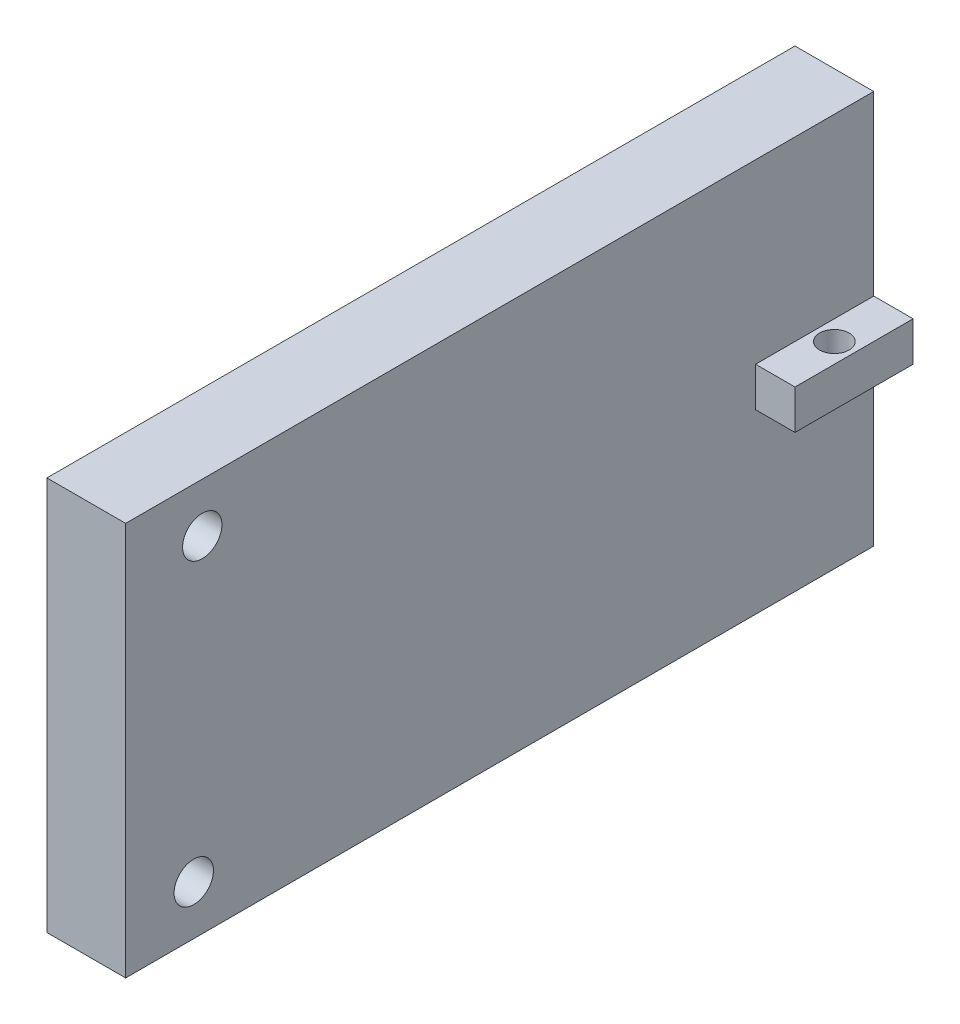
SolidWorks part; units mm, degrees
ref_plane "Front Plane" through (0, 0, 0) normal (0, 0, 1) x (1, 0, 0)
ref_plane "Top Plane" through (0, 0, 0) normal (0, 1, 0) x (1, 0, 0)
ref_plane "Right Plane" through (0, 0, 0) normal (1, 0, 0) x (0, 0, -1)
sketch "Sketch3" plane through (0, 0, 0) normal (1, 0, 0) x (0, 0, -1)
  line L1 (-250.0536, 744.7533) -> (715.1464, 744.7533)
  line L2 (-250.0536, 744.7533) -> (-250.0536, 236.7533)
  line L3 (-250.0536, 236.7533) -> (715.1464, 236.7533)
  line L4 (715.1464, 744.7533) -> (715.1464, 236.7533)
  dimension "D1" = 965.2
  dimension "D2" = 508
extrude "Boss-Extrude2" add sketch "Sketch3" along normal blind 101.6
sketch "Sketch4" plane through (0, 0, 0) normal (1, 0, 0) x (0, 0, -1)
  line L0 (-250.0536, 236.7533) -> (715.1464, 236.7533) construction
  circle A0 centre (-151.2172, 681.2533) radius 25.4
  circle A1 centre (-162.1819, 300.2533) radius 25.4
  dimension "D1" = 50.8
  dimension "D2" = 50.8
  dimension "D3" = 381
  dimension "D4" = 63.5
extrude "Cut-Extrude2" cut sketch "Sketch4" along normal blind 101.6
sketch "Sketch7" plane through (0, 0, 0) normal (1, 0, 0) x (0, 0, -1)
  line L0 (715.1464, 236.7533) -> (715.1464, 744.7533) construction
  line L1 (715.1464, 516.1533) -> (562.7464, 516.1533)
  line L2 (715.1464, 516.1533) -> (715.1464, 465.3533)
  line L3 (715.1464, 465.3533) -> (562.7464, 465.3533)
  line L4 (562.7464, 516.1533) -> (562.7464, 465.3533)
  dimension "D1" = 50.8
  dimension "D2" = 152.4
  dimension "D3" = 228.6
extrude "Boss-Extrude4" add sketch "Sketch7" along normal blind 152.4
sketch "Sketch10" plane through (0, 0, 0) normal (0, 1, 0) x (1, 0, 0)
  line L0 (152.4, 562.7464) -> (101.6, 562.7464) construction
  line L3 (101.6, -250.0536) -> (101.6, 715.1464) construction
  circle A0 centre (127, 638.9464) radius 19.05
  dimension "D1" = 38.1
  dimension "D2" = 76.2
  dimension "D3" = 25.4
extrude "Cut-Extrude3" cut sketch "Sketch10" along normal blind 609.6
sketch "Sketch11" plane through (0, 0, 0) normal (1, 0, 0) x (0, 0, -1)
  line L0 (-250.0536, 490.7533) -> (715.1464, 490.7533) construction
  line L1 (-250.0536, 744.7533) -> (-250.0536, 236.7533) construction
  line L2 (715.1464, 236.7533) -> (715.1464, 744.7533) construction
sketch "Sketch12" plane through (0, 0, 0) normal (1, 0, 0) x (0, 0, -1)
  line L0 (-250.0536, 490.7533) -> (715.1464, 490.7533) construction
  point P0 (232.5464, 490.7533)
